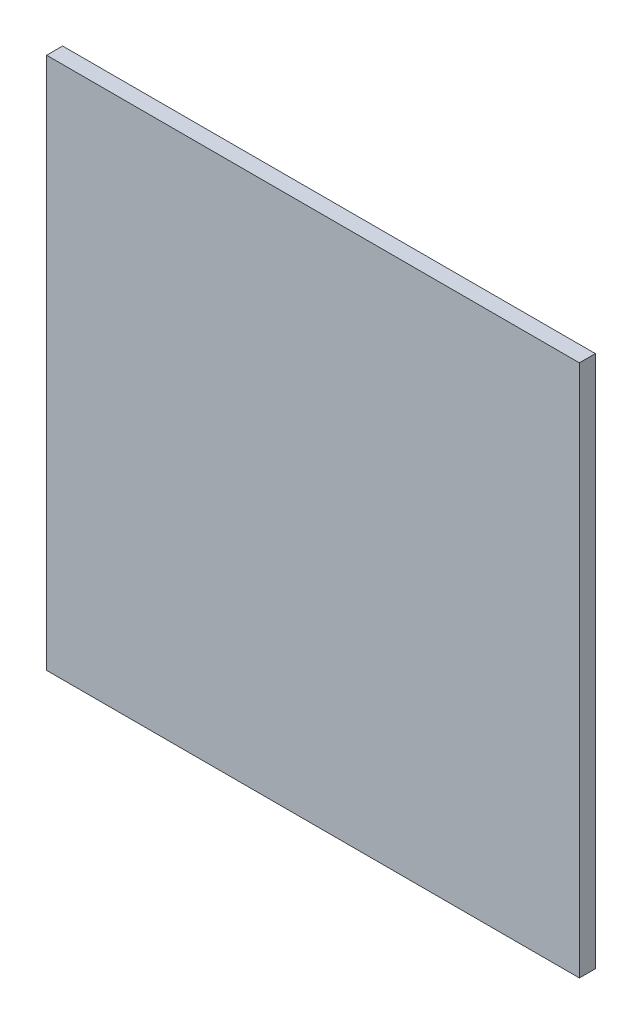
SolidWorks part; units mm, degrees
ref_plane "Front Plane" through (0, 0, 0) normal (0, 0, 1) x (1, 0, 0)
ref_plane "Top Plane" through (0, 0, 0) normal (0, 1, 0) x (1, 0, 0)
ref_plane "Right Plane" through (0, 0, 0) normal (1, 0, 0) x (0, 0, -1)
sketch "Sketch2" plane through (0, 0, 0) normal (0, 0, 1) x (1, 0, 0)
  line L1 (-50, -50) -> (50, -50)
  line L2 (-50, -50) -> (-50, 50)
  line L3 (-50, 50) -> (50, 50)
  line L4 (50, -50) -> (50, 50)
  line L5 (-50, -50) -> (50, 50) construction
  line L6 (-50, 50) -> (50, -50) construction
  point P0 (0, 0)
  dimension "D1" = 100
  dimension "D2" = 100
extrude "Boss-Extrude1" add sketch "Sketch2" along normal blind 3
